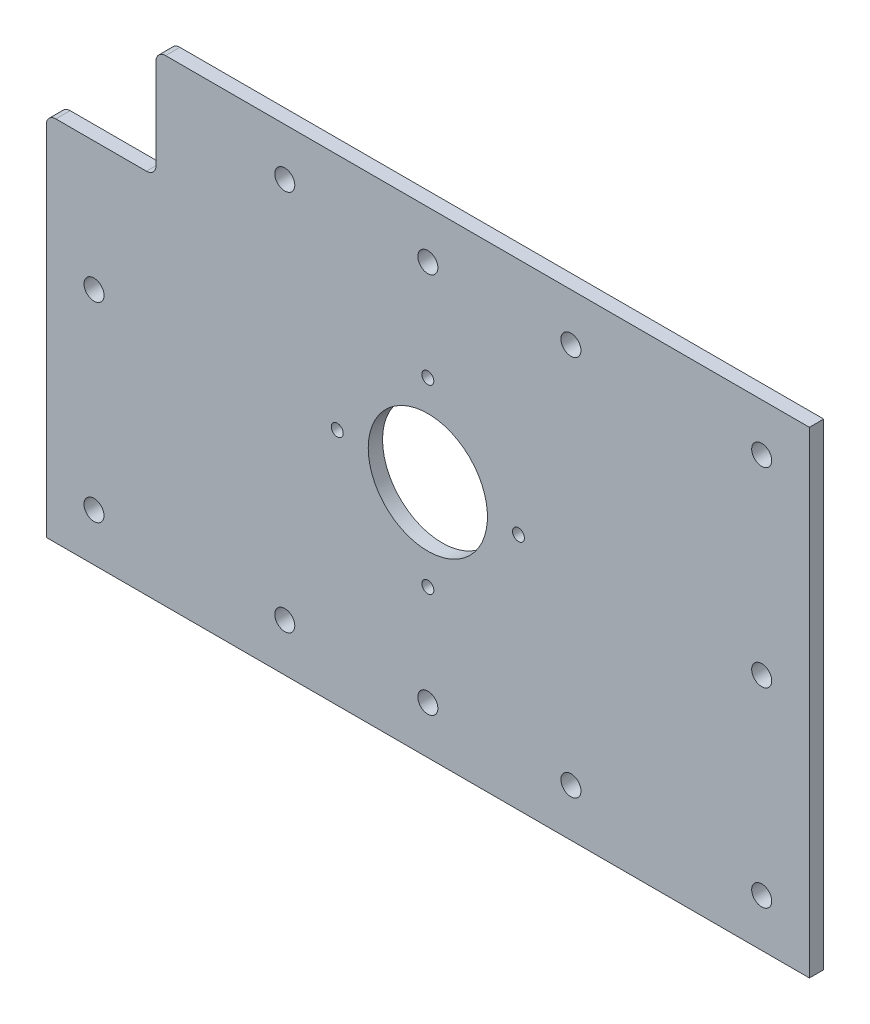
SolidWorks part; units mm, degrees
material "黑玻纤板"
ref_plane "前视基准面" through (0, 0, 0) normal (0, 0, 1) x (1, 0, 0)
ref_plane "上视基准面" through (0, 0, 0) normal (0, 1, 0) x (1, 0, 0)
ref_plane "右视基准面" through (0, 0, 0) normal (1, 0, 0) x (0, 0, -1)
sketch "草图1" plane through (0, 0, 0) normal (0, 0, 1) x (1, 0, 0)
  line L1 (-80, 50) -> (80, 50)
  line L2 (-80, 50) -> (-80, -50)
  line L3 (-80, -50) -> (80, -50)
  line L4 (80, 50) -> (80, -50)
  line L5 (-80, 50) -> (80, -50) construction
  line L6 (-80, -50) -> (80, 50) construction
  point P0 (0, 0)
  dimension "D1" = 160
  dimension "D2" = 100
extrude "凸台-拉伸1" add sketch "草图1" along normal blind 3
sketch "草图2" plane through (0, 0, 3) normal (0, 0, 1) x (1, 0, 0)
  line L0 (80, 40) -> (-80, 40) construction
  line L1 (80, -50) -> (80, 50) construction
  line L2 (-80, 50) -> (-80, -50) construction
  line L3 (80, 50) -> (-80, 50) construction
  line L4 (-70, 50) -> (-70, -50) construction
  line L5 (-80, -50) -> (80, -50) construction
  line L6 (0, 50) -> (0, -50) construction
  line L7 (70, 50) -> (70, -50) construction
  line L8 (80, 0) -> (-80, 0) construction
  line L9 (80, -40) -> (-80, -40) construction
  circle A0 centre (-70, 40) radius 2.1
  circle A1 centre (-30, 40) radius 2.1
  circle A2 centre (0, 40) radius 2.1
  circle A3 centre (30, 40) radius 2.1
  circle A4 centre (70, 40) radius 2.1
  circle A5 centre (-70, 0) radius 2.1
  circle A6 centre (-70, -40) radius 2.1
  circle A7 centre (-70, -80) radius 2.1
  circle A8 centre (-70, -120) radius 2.1
  circle A9 centre (-70, -160) radius 2.1
  circle A10 centre (-70, -200) radius 2.1
  circle A11 centre (-70, -240) radius 2.1
  circle A12 centre (-70, -280) radius 2.1
  circle A13 centre (70, -280) radius 2.1
  circle A14 centre (70, -240) radius 2.1
  circle A15 centre (70, -200) radius 2.1
  circle A16 centre (70, -160) radius 2.1
  circle A17 centre (70, -120) radius 2.1
  circle A18 centre (70, -80) radius 2.1
  circle A19 centre (70, -40) radius 2.1
  circle A20 centre (70, 0) radius 2.1
  circle A21 centre (70, 40) radius 2.1
  circle A22 centre (30, -40) radius 2.1
  circle A23 centre (0, -40) radius 2.1
  circle A24 centre (-30, -40) radius 2.1
  dimension "D3" = 4.2
  dimension "D4" = 40
  dimension "D7" = 40
  dimension "D1" = 10
  dimension "D2" = 10
  dimension "D5" = 30
  dimension "D6" = 30
  dimension "D8" = 9
extrude "切除-拉伸1" cut sketch "草图2" against normal through all contours A24 | A12 | A11 | A23 | A22 | A13 | A14 | A15 | A10 | A9 | A8 | A16 | A17 | A18 | A19 | A20 | A3 | A2 | A1 | A0 | A5 | A7 | A6 | A4
sketch "草图3" plane through (0, 0, 0) normal (0, 0, -1) x (-1, 0, 0)
  line L0 (0, 65) -> (0, -65) construction
  line L1 (80, 0) -> (-80, 0) construction
  line L2 (80, 50) -> (80, -50) construction
  line L3 (-80, -50) -> (-80, 50) construction
  circle A0 centre (0, 0) radius 19 construction
  circle A1 centre (19, 0) radius 1.25
  circle A2 centre (0, -19) radius 1.25
  circle A3 centre (-19, 0) radius 1.25
  circle A4 centre (0, 19) radius 1.25
  point P2 (0, 0)
  dimension "D1" = 38
  dimension "D2" = 2.5
  dimension "D4" = 80
  dimension "D3" = 4
extrude "切除-拉伸2" cut sketch "草图3" against normal through all both and the other way through all
sketch "草图4" plane through (0, 0, 0) normal (0, 0, -1) x (-1, 0, 0)
  line L0 (19, 0) -> (-19, 0) construction
  circle A0 centre (0, 0) radius 12.5
  circle A1 centre (0, 0) radius 19 construction
  point P6 (0, 0)
  point P10 (0, 0)
  point P11 (0, 0)
  dimension "D1" = 25
extrude "切除-拉伸3" cut sketch "草图4" against normal through all both and the other way through all
sketch "草图5" plane through (0, 0, 3) normal (0, 0, 1) x (1, 0, 0)
  line L1 (-80, 50) -> (-57, 50)
  line L2 (-80, 50) -> (-80, 27)
  line L3 (-80, 27) -> (-57, 27)
  line L4 (-57, 50) -> (-57, 27)
  dimension "D1" = 23
  dimension "D2" = 23
extrude "切除-拉伸4" cut sketch "草图5" against normal through all both and the other way through all
fillet "圆角1" radius 2 3 edges at (-57, 50, 1.5) (-80, 27, 1.5) (-57, 27, 1.5)
